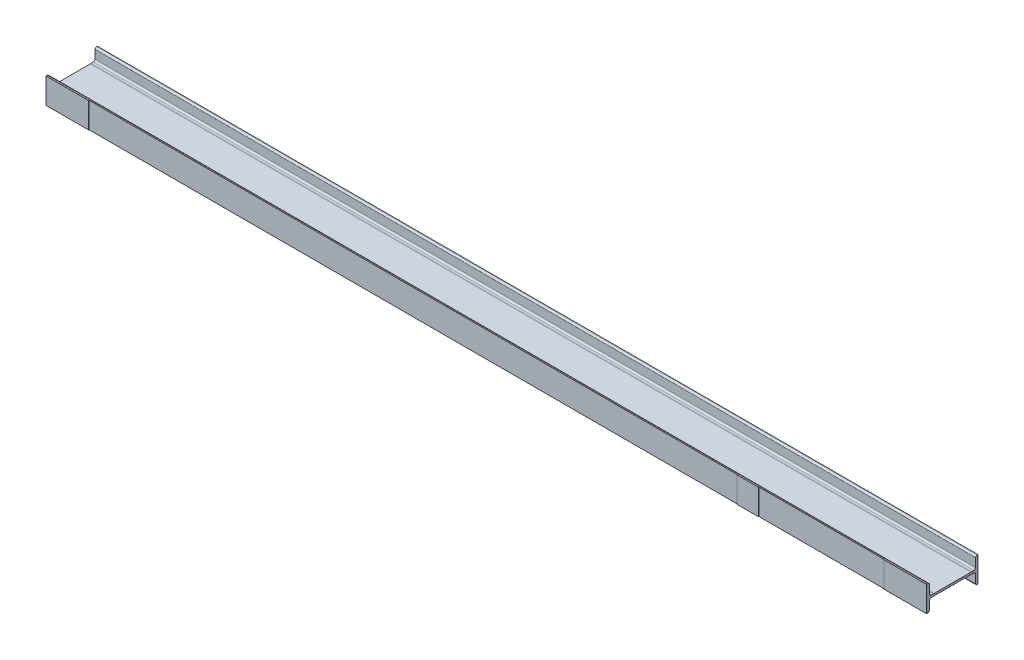
SolidWorks part; units mm, degrees
material "Hierro dúctil"
ref_plane "Alzado" through (0, 0, 0) normal (0, 0, 1) x (1, 0, 0)
ref_plane "Planta" through (0, 0, 0) normal (0, 1, 0) x (1, 0, 0)
ref_plane "Vista lateral" through (0, 0, 0) normal (1, 0, 0) x (0, 0, -1)
sketch "Croquis1" plane through (0, 0, 0) normal (0, 0, 1) x (1, 0, 0)
  line L0 (0, 0) -> (2070, 0)
  dimension "D1" = 2070
other "Viga sb 120 X 12(2)"
ref_plane "Plano1" through (0, 0, 0) normal (1, 0, 0) x (0, 1, 0)
sketch "Sketch12" plane through (0, 0, 0) normal (1, 0, 0) x (0, 1, 0)
  line L0 (-30, -60) -> (-30, -58.0801)
  line L1 (-26.6576, -54.1345) -> (-9.1847, -51.2221)
  line L2 (-2.5, -43.331) -> (-2.5, 43.331)
  line L3 (-9.1847, 51.2221) -> (-26.6576, 54.1345)
  line L4 (-30, 58.0801) -> (-30, 60)
  line L5 (-30, 60) -> (30, 60)
  line L6 (30, 60) -> (30, 58.0801)
  line L7 (26.6576, 54.1345) -> (9.1847, 51.2221)
  line L8 (2.5, 43.331) -> (2.5, -43.331)
  line L9 (9.1847, -51.2221) -> (26.6576, -54.1345)
  line L10 (30, -58.0801) -> (30, -60)
  line L11 (30, -60) -> (-30, -60)
  line L15 (-2.5, 0) -> (2.5, 0) construction
  arc A0 (-9.1847, -51.2221) -> (-2.5, -43.331) centre (-10.5, -43.331) ccw
  arc A1 (-2.5, 43.331) -> (-9.1847, 51.2221) centre (-10.5, 43.331) ccw
  arc A2 (9.1847, 51.2221) -> (2.5, 43.331) centre (10.5, 43.331) ccw
  arc A3 (2.5, -43.331) -> (9.1847, -51.2221) centre (10.5, -43.331) ccw
  arc A4 (-26.6576, 54.1345) -> (-30, 58.0801) centre (-26, 58.0801) cw
  arc A5 (26.6576, 54.1345) -> (30, 58.0801) centre (26, 58.0801) ccw
  arc A6 (-30, -58.0801) -> (-26.6576, -54.1345) centre (-26, -58.0801) cw
  arc A7 (30, -58.0801) -> (26.6576, -54.1345) centre (26, -58.0801) ccw
  point P1 (0, 60)
  point P8 (0, -60)
  point P21 (0, 0)
  point P34 (0, 0)
  dimension "RI" = 8
  dimension "D3" = 4
  dimension "BF" = 60
  dimension "D2" = 9.463
  dimension "DEPTH" = 120
  dimension "TW" = 5
  dimension "D1" = 86.662
sketch "Croquis3" plane through (0, 0, 0) normal (-1, 0, 0) x (0, 0, 1)
  line L0 (0, 0) -> (0, 20.5092) construction
  line L1 (54.1345, 26.6576) -> (44.9002, 26.6576)
  line L2 (54.1345, 26.6576) -> (54.1345, 6.6554)
  line L3 (50.1345, 2.6554) -> (44.9002, 2.6554)
  line L4 (44.9002, 26.6576) -> (44.9002, 2.6554)
  line L5 (54.1345, -26.6576) -> (43.331, -26.6576)
  line L6 (54.1345, -26.6576) -> (54.1345, -6.5)
  line L7 (50.1345, -2.5) -> (43.331, -2.5)
  line L8 (43.331, -26.6576) -> (43.331, -2.5)
  line L9 (-43.331, -26.6576) -> (-43.331, -2.5)
  line L10 (-50.1345, -2.5) -> (-43.331, -2.5)
  line L11 (-54.1345, -26.6576) -> (-54.1345, -6.5)
  line L12 (-54.1345, -26.6576) -> (-43.331, -26.6576)
  line L13 (-44.9002, 26.6576) -> (-44.9002, 2.6554)
  line L14 (-50.1345, 2.6554) -> (-44.9002, 2.6554)
  line L15 (-54.1345, 26.6576) -> (-54.1345, 6.6554)
  line L16 (-54.1345, 26.6576) -> (-44.9002, 26.6576)
  arc A1 (43.331, 2.5) -> (51.2221, 9.1847) centre (43.331, 10.5) ccw construction
  arc A2 (54.1345, -6.5) -> (50.1345, -2.5) centre (50.1345, -6.5) ccw
  arc A3 (50.1345, 2.6554) -> (54.1345, 6.6554) centre (50.1345, 6.6554) ccw
  arc A4 (-54.1345, -6.5) -> (-50.1345, -2.5) centre (-50.1345, -6.5) cw
  arc A5 (-50.1345, 2.6554) -> (-54.1345, 6.6554) centre (-50.1345, 6.6554) cw
  point P30 (54.1345, -2.5)
  point P33 (54.1345, 2.6554)
  point P36 (-54.1345, -2.5)
  point P39 (-54.1345, 2.6554)
  dimension "D5" = 4
  dimension "D1" = 24.0022
  dimension "D2" = 9.2343
  dimension "D3" = 24.1576
  dimension "D4" = 10.8035
extrude "Cortar-Extruir1" cut sketch "Croquis3" against normal through all both and the other way through all
sketch "Croquis4" plane through (0, 0, 60) normal (0, 0, 1) x (1, 0, 0)
  line L0 (2070, 30) -> (0, 30) construction
  line L1 (1624.8292, -30) -> (1675.1708, -30)
  line L2 (1624.8292, -30) -> (1624.8292, 30)
  line L3 (1624.8292, 30) -> (1675.1708, 30)
  line L4 (1675.1708, -30) -> (1675.1708, 30)
  line L5 (1624.8292, -30) -> (1675.1708, 30) construction
  line L6 (1624.8292, 30) -> (1675.1708, -30) construction
  point P0 (1650, 0)
  dimension "D1" = 60
  dimension "D2" = 50.3417
  dimension "D3" = 1650
extrude "Saliente-Extruir1" add sketch "Croquis4" along normal blind 1 separate body
sketch "Croquis6" plane through (0, 0, 60) normal (0, 0, 1) x (1, 0, 0)
  line L2 (2070, 30) -> (1970, 30)
  line L3 (2070, 30) -> (2070, -30)
  line L4 (2070, -30) -> (1970, -30)
  line L5 (2070, -30) -> (0, -30) construction
  line L7 (1970, 30) -> (1970, -30)
  line L8 (0, 30) -> (100, 30)
  line L9 (0, 30) -> (0, -30)
  line L10 (0, -30) -> (100, -30)
  line L12 (100, 30) -> (100, -30)
  dimension "D1" = 60
  dimension "D2" = 60
  dimension "D3" = 100
  dimension "D4" = 100
extrude "Saliente-Extruir2" add sketch "Croquis6" along normal blind 1 separate body
sketch "Croquis7" plane through (0, 0, 0) normal (-1, 0, 0) x (0, 0, 1)
  line L1 (54.1345, -6.6554) -> (-54.1345, -6.6554)
  line L2 (54.1345, -6.6554) -> (54.1345, 6.6554)
  line L3 (54.1345, 6.6554) -> (-54.1345, 6.6554)
  line L4 (-54.1345, -6.6554) -> (-54.1345, 6.6554)
  line L5 (54.1345, -6.6554) -> (-54.1345, 6.6554) construction
  line L6 (54.1345, 6.6554) -> (-54.1345, -6.6554) construction
  point P0 (0, 0)
  dimension "D1" = 13.3108
  dimension "D2" = 108.269
extrude "Saliente-Extruir3" [suppressed] add sketch "Croquis7" against normal blind 100
sketch "Croquis8" plane through (2070, 0, 0) normal (1, 0, 0) x (0, 0, -1)
  line L1 (-54.1345, 6.5) -> (54.1345, 6.5)
  line L2 (-54.1345, 6.5) -> (-54.1345, -6.5)
  line L3 (-54.1345, -6.5) -> (54.1345, -6.5)
  line L4 (54.1345, 6.5) -> (54.1345, -6.5)
  line L5 (-54.1345, 6.5) -> (54.1345, -6.5) construction
  line L6 (-54.1345, -6.5) -> (54.1345, 6.5) construction
  point P0 (0, 0)
  dimension "D1" = 13
  dimension "D2" = 108.269
extrude "Saliente-Extruir4" [suppressed] add sketch "Croquis8" against normal blind 100
